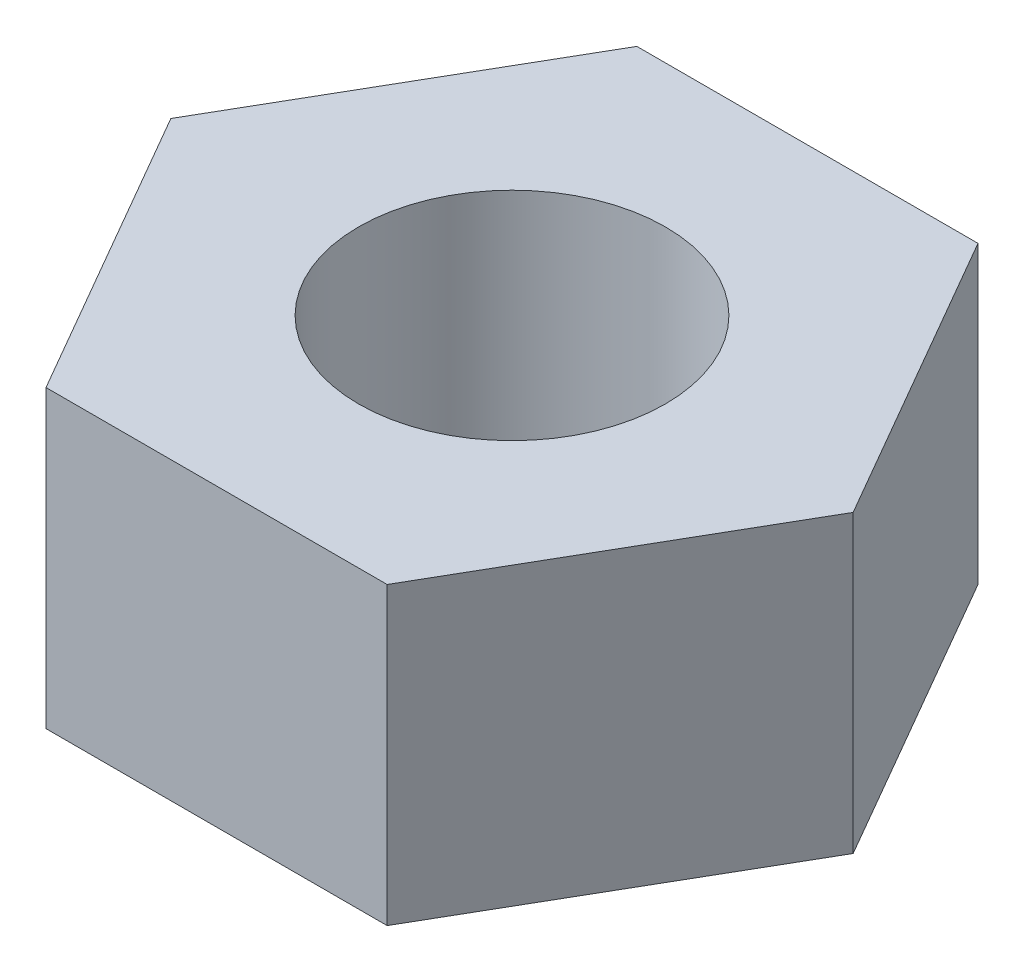
SolidWorks part; units mm, degrees
material "acero"
ref_plane "Alzado" through (0, 0, 0) normal (0, 0, 1) x (1, 0, 0)
ref_plane "Planta" through (0, 0, 0) normal (0, 1, 0) x (1, 0, 0)
ref_plane "Vista lateral" through (0, 0, 0) normal (1, 0, 0) x (0, 0, -1)
sketch "Croquis1" plane through (0, 0, 0) normal (0, 1, 0) x (1, 0, 0)
  line L1 (-3.7528, 6.5) -> (-7.5056, 0)
  line L2 (-7.5056, 0) -> (-3.7528, -6.5)
  line L3 (-3.7528, -6.5) -> (3.7528, -6.5)
  line L4 (3.7528, -6.5) -> (7.5056, 0)
  line L5 (7.5056, 0) -> (3.7528, 6.5)
  line L6 (3.7528, 6.5) -> (-3.7528, 6.5)
  circle A0 centre (0, 0) radius 6.5 construction
  circle A1 centre (0, 0) radius 3.375
  dimension "D1" = 6.75
  dimension "D2" = 13
extrude "Saliente-Extruir1" add sketch "Croquis1" along normal blind 6.5
